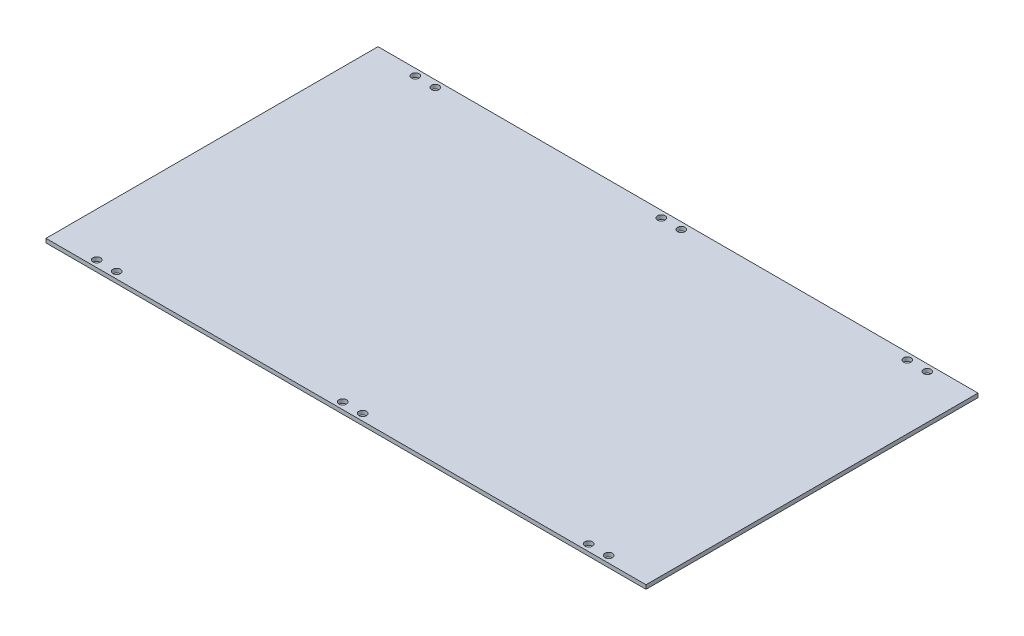
SolidWorks part; units mm, degrees
material "AISI 316 Arkusz stali nierdzewnej (SS)"
ref_plane "Płaszczyzna przednia" through (0, 0, 0) normal (0, 0, 1) x (1, 0, 0)
ref_plane "Płaszczyzna górna" through (0, 0, 0) normal (0, 1, 0) x (1, 0, 0)
ref_plane "Płaszczyzna prawa" through (0, 0, 0) normal (1, 0, 0) x (0, 0, -1)
sketch "Szkic3" plane through (0, 0, 0) normal (0, 1, 0) x (1, 0, 0)
  line L1 (-150, -83) -> (150, -83)
  line L2 (-150, -83) -> (-150, 83)
  line L3 (-150, 83) -> (150, 83)
  line L4 (150, -83) -> (150, 83)
  line L5 (-150, -83) -> (150, 83) construction
  line L6 (-150, 83) -> (150, -83) construction
  point P0 (0, 0)
  dimension "D1" = 166
  dimension "D2" = 300
extrude "Dodanie-wyciągnięcie2" add sketch "Szkic3" along normal blind 2
sketch "Szkic4" plane through (0, 2, 0) normal (0, 1, 0) x (1, 0, 0)
  line L0 (-150, -83) -> (150, -83) construction
  line L1 (150, -83) -> (150, 83) construction
  line L2 (-150, 0) -> (150, 0) construction
  line L3 (-150, 83) -> (-150, -83) construction
  line L4 (0, 83) -> (0, -83) construction
  line L5 (150, 83) -> (-150, 83) construction
  line L6 (-5, -79.65) -> (5, -79.65) construction
  line L7 (118, -79.65) -> (128, -79.65) construction
  circle A0 centre (128, -79.65) radius 1.9
  circle A1 centre (118, -79.65) radius 1.9
  circle A2 centre (118, 79.65) radius 1.9
  circle A3 centre (128, 79.65) radius 1.9
  circle A4 centre (-118, -79.65) radius 1.9
  circle A5 centre (-128, -79.65) radius 1.9
  circle A6 centre (-128, 79.65) radius 1.9
  circle A7 centre (-118, 79.65) radius 1.9
  circle A8 centre (5, -79.65) radius 1.9
  circle A9 centre (-5, -79.65) radius 1.9
  circle A10 centre (5, 79.65) radius 1.9
  circle A11 centre (-5, 79.65) radius 1.9
  point P30 (-5, -79.65)
  dimension "D1" = 3.8
  dimension "D4" = 10
  dimension "D2" = 3.35
  dimension "D3" = 22
extrude "Wytnij-wyciągnięcie1" cut sketch "Szkic4" along direction (0, -1, 0) on the side against the normal up to next (2 mm away)
